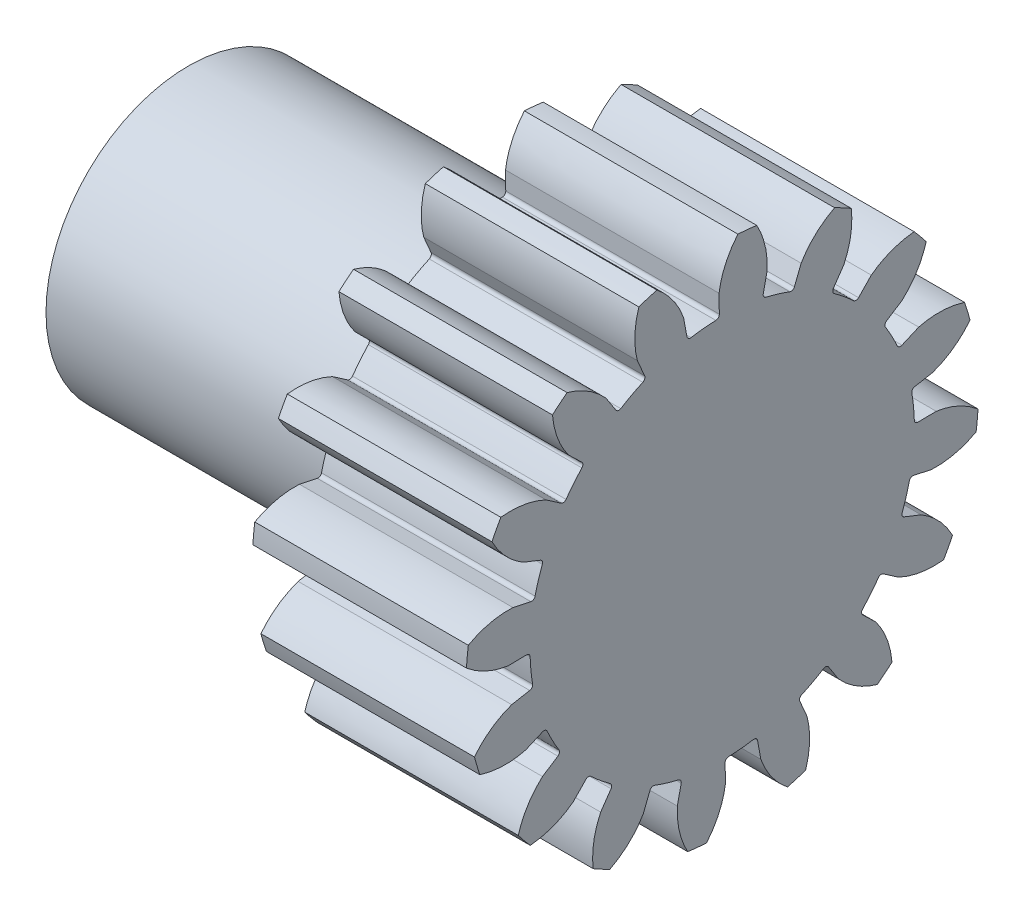
SolidWorks part; units mm, degrees
ref_plane "Спереди" through (0, 0, 0) normal (0, 0, 1) x (1, 0, 0)
ref_plane "Сверху" through (0, 0, 0) normal (0, 1, 0) x (1, 0, 0)
ref_plane "Справа" through (0, 0, 0) normal (1, 0, 0) x (0, 0, -1)
sketch "Эскиз2" plane through (0, 0, 0) normal (1, 0, 0) x (0, 0, -1)
  circle A0 centre (0, 0) radius 5.4
  dimension "D1" = 10.8
extrude "Бобышка-Вытянуть2" add sketch "Эскиз2" along normal blind 6
sketch "Эскиз5" plane through (0, 0, 0) normal (-1, 0, 0) x (0, 0, 1)
  circle A0 centre (0, 0) radius 4
  dimension "D1" = 8
extrude "Бобышка-Вытянуть4" add sketch "Эскиз5" along normal blind 9
hole_wizard "Отверстие обработанное метчиком M31" positions "Эскиз6" profile "Эскиз7" tap size "M3" standard "ISO"
sketch "Эскиз6" plane through (-9, 0, 0) normal (-1, 0, 0) x (0, 0, 1)
  point P0 (0, 0)
sketch "Эскиз7" plane through (-9, 0, 0) normal (0, 1, 0) x (0, 0, 1)
  line L0 (0, 0) -> (0, 9.2511)
  line L1 (0, 9.2511) -> (1.25, 8.5)
  line L2 (1.25, 8.5) -> (1.25, 1.25)
  line L3 (1.25, 1.25) -> (2.5, 0)
  line L5 (2.5, 0) -> (0, 0)
  line L6 (-1.25, 1.25) -> (-2.5, 0) construction
  line L10 (0, 9.2511) -> (-1.25, 8.5) construction
  line L11 (0, -6.35) -> (0, 107.95) construction
  dimension "Диаметр сверла" = 2.5
  dimension "Глубина сверла" = 8.5
  dimension "Диаметр передней зенковки" = 5
  dimension "Угол передней зенковки" = 90
  dimension "Угол заточки сверла" = 118
cosmetic thread "Отверстие резьбы1" parameters "D1"=0, "D2"=3.5
ref_plane "Плоскость2" through (3, 0, 0) normal (1, 0, 0) x (0, 0, -1)
sketch "Эскиз9" plane through (3, 0, 0) normal (1, 0, 0) x (0, 0, -1)
  line L0 (0, 0) -> (0, 6.4) construction
  line L1 (0, 6.4) -> (1.2306, 6.4) construction
  line L2 (0, 6.4) -> (2.0569, 5.6513) construction
  line L3 (0.4403, 7.1865) -> (3.6077, 4.8118) construction
  line L4 (0, 0) -> (-0.0896, 6.0134) construction
  line L5 (-0.0896, 6.0134) -> (-0.0805, 5.3994)
  line L6 (0, 0) -> (0.7057, 7.1653) construction
  line L7 (1.2611, 5.8803) -> (1.1323, 5.28)
  arc A0 (0.9702, 7.1343) -> (0.4403, 7.1865) centre (0, 0) ccw
  circle A1 centre (0, 0) radius 6.4 construction
  circle A2 centre (0, 0) radius 5.4 construction
  arc A3 (1.1323, 5.28) -> (-0.0805, 5.3994) centre (0, 0) ccw
  circle A4 centre (0, 0) radius 6.014 construction
  spline S0 degree 2 poles (-0.0896, 6.0134) (0.0048, 6.6659) (0.4403, 7.1865) knots 0 0 0 1 1 1
  spline S1 degree 2 poles (1.2611, 5.8803) (1.2957, 6.5388) (0.9702, 7.1343) knots 0 0 0 1 1 1
  point P11 (-0.0896, 6.0134)
  dimension "D1" = 12.8
  dimension "D2" = 14.4
  dimension "D3" = 20
  dimension "D4" = 2.1889
  dimension "D5" = 3.9587
  dimension "D8" = 5.625
  dimension "D6" = 1.7698
  dimension "D7" = 2.1889
extrude "Бобышка-Вытянуть5" add sketch "Эскиз9" along normal up to surface and the other way up to surface up to face at (6, 0, -5.4) other way up to face at (0, 0, 4)
fillet "Скругление4" radius 0.1 2 edges at (3, 5.3994, 0.0805) (3, 5.28, -1.1323)
pattern_circular "Круговой массив1" count 16 over 360 about axis through (6, 0, 0) along (-1, 0, 0) of "Бобышка-Вытянуть5", "Скругление4"
sketch "Эскиз11" plane through (0, 0, 0) normal (0, 0, 1) x (1, 0, 0)
  line L0 (0, 4) -> (0, 3.7)
  line L1 (0, 3.7) -> (-0.5, 3.7)
  line L2 (-0.5, 3.7) -> (-0.8, 4)
  line L3 (0, 4) -> (-9, 4) construction
  line L4 (-0.8, 4) -> (0, 4)
  dimension "D1" = 0.3
  dimension "D2" = 0.8
  dimension "D3" = 45
revolve "Вырез-Повернуть3" cut sketch "Эскиз11" angle 360 about axis through (-9, 0, 0) along (1, 0, 0)
fillet "Скругление5" radius 0.2 2 edges at (-0.5, 0, 3.7) (0, 0, 3.7)
equation "\"Модуль\"= 0.8мм"
equation "\"Число2\"= 16"
equation "\"D1@Эскиз2\"= \"Модуль\" * (\"Число2\" - 2.5)"
equation "\"D1@Эскиз9\"= \"Модуль\" * \"Число2\""
equation "\"D2@Эскиз9\"= \"Модуль\" * (\"Число2\" + 2)"
equation "\"D6@Эскиз9\"= \"D5@Эскиз9\" - \"D4@Эскиз9\""
equation "\"D7@Эскиз9\"= \"D4@Эскиз9\""
equation "\"D8@Эскиз9\"= 90 / \"Число2\""
equation "\"D1@Круговой массив1\"= \"Число2\""
